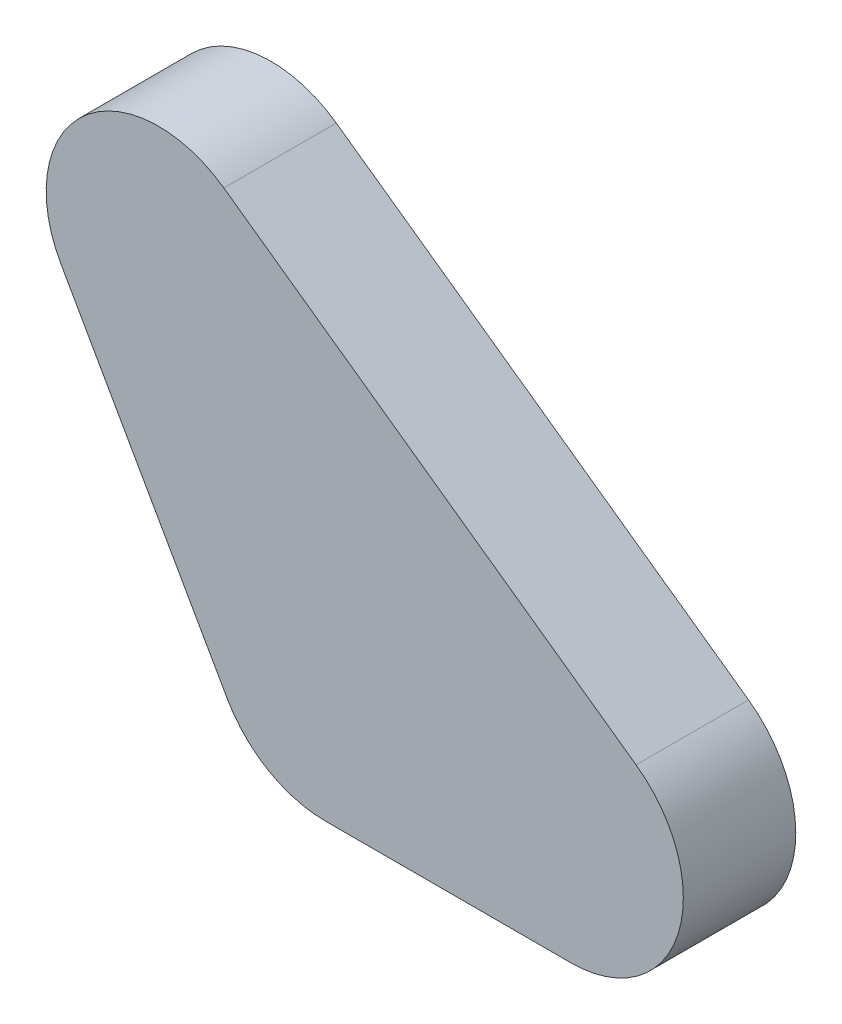
SolidWorks part; units mm, degrees
ref_plane "前视基准面" through (0, 0, 0) normal (0, 0, 1) x (1, 0, 0)
ref_plane "上视基准面" through (0, 0, 0) normal (0, 1, 0) x (1, 0, 0)
ref_plane "右视基准面" through (0, 0, 0) normal (1, 0, 0) x (0, 0, -1)
other "Configuration Table"
sketch "草图1" plane through (0, 0, 0) normal (0, 0, 1) x (1, 0, 0)
  line L0 (14.7977, -36.0965) -> (36.6602, -36.0965)
  line L1 (6.0989, -31.0291) -> (-8.6988, -4.9326)
  line L2 (42.4595, -17.9498) -> (5.7992, 8.1467)
  arc A0 (36.6602, -36.0965) -> (42.4595, -17.9498) centre (36.6602, -26.0965) ccw
  arc A1 (14.7977, -36.0965) -> (6.0989, -31.0291) centre (14.7977, -26.0965) cw
  arc A2 (5.7992, 8.1467) -> (-8.6988, -4.9326) centre (0, 0) ccw
  point P9 (0, 0)
  point P10 (0, 0)
  dimension "D3" = 10
  dimension "D4" = 25
  dimension "D1" = 45
  dimension "D2" = 30
extrude "凸台-拉伸1" add sketch "草图1" along normal blind 10
